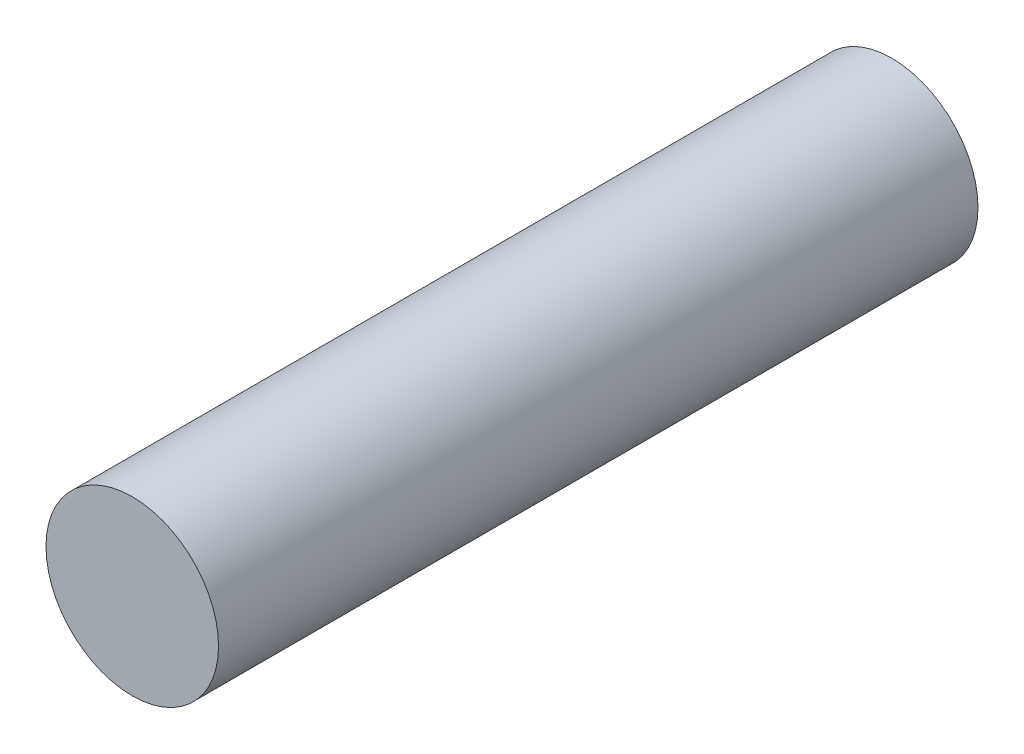
SolidWorks part; units mm, degrees
material "Alloy Steel (SS)"
ref_plane "Front Plane" through (0, 0, 0) normal (0, 0, 1) x (1, 0, 0)
ref_plane "Top Plane" through (0, 0, 0) normal (0, 1, 0) x (1, 0, 0)
ref_plane "Right Plane" through (0, 0, 0) normal (1, 0, 0) x (0, 0, -1)
sketch "Sketch2" plane through (0, 0, 0) normal (0, 0, 1) x (1, 0, 0)
  circle A0 centre (0, 0) radius 3.975
  dimension "D1" = 7.95
extrude "Boss-Extrude1" add sketch "Sketch2" along normal blind 35
